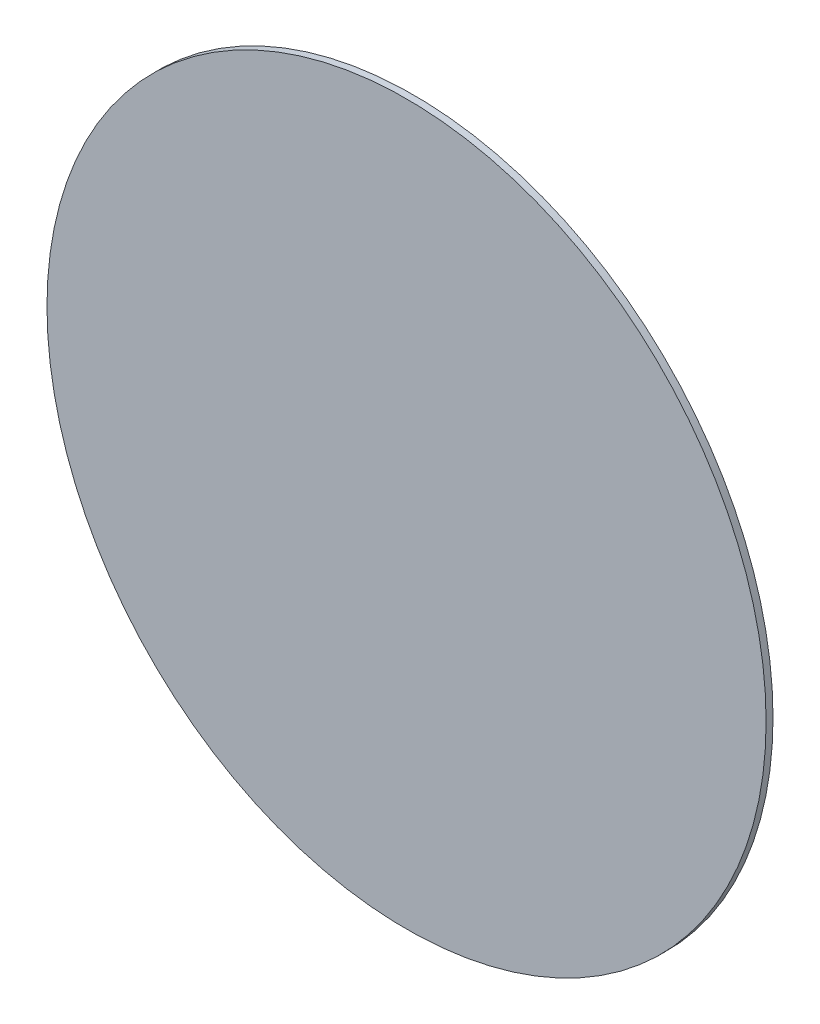
SolidWorks part; units mm, degrees
material "Alloy Steel"
ref_plane "Front Plane" through (0, 0, 0) normal (0, 0, 1) x (1, 0, 0)
ref_plane "Top Plane" through (0, 0, 0) normal (0, 1, 0) x (1, 0, 0)
ref_plane "Right Plane" through (0, 0, 0) normal (1, 0, 0) x (0, 0, -1)
sketch "Sketch1" plane through (0, 0, 0) normal (0, 0, 1) x (1, 0, 0)
  circle A0 centre (0, 0) radius 26
  dimension "D1" = 52
extrude "Boss-Extrude1" add sketch "Sketch1" along normal blind 0.5
